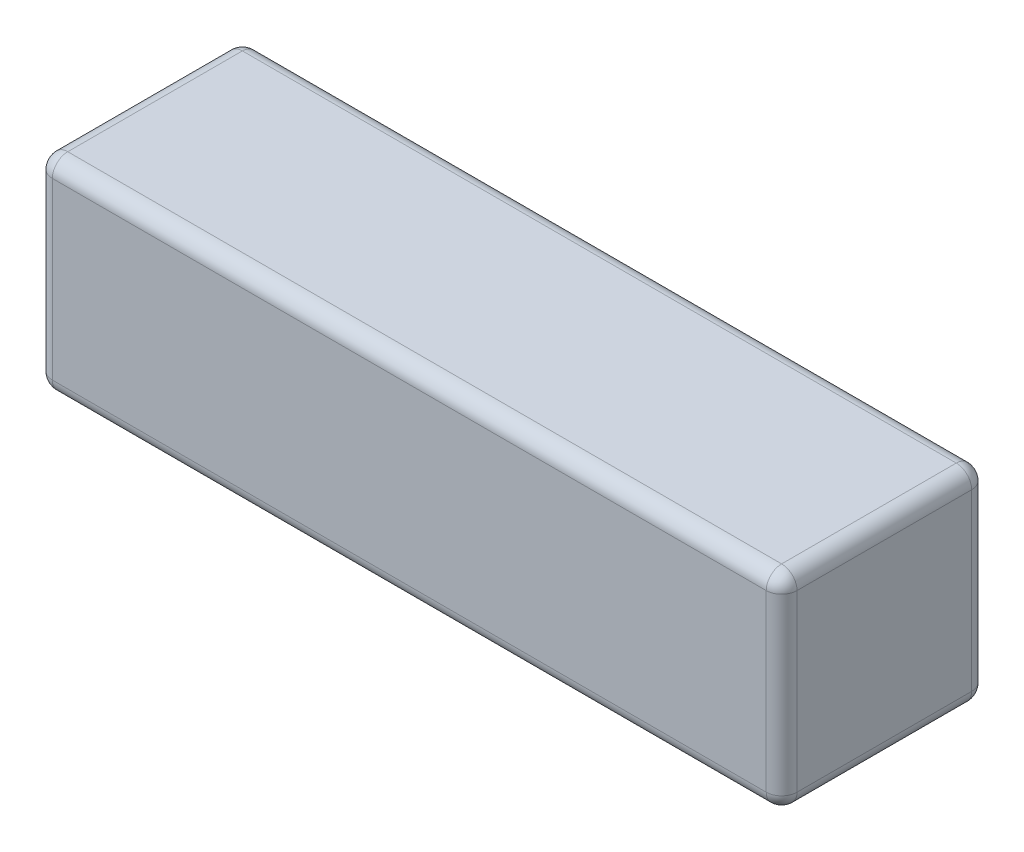
SolidWorks part; units mm, degrees
ref_plane "Front" through (0, 0, 0) normal (0, 0, 1) x (1, 0, 0)
ref_plane "Top" through (0, 0, 0) normal (0, 1, 0) x (1, 0, 0)
ref_plane "Right" through (0, 0, 0) normal (1, 0, 0) x (0, 0, -1)
sketch "草图1" plane through (0, 0, 0) normal (0, 1, 0) x (1, 0, 0)
  line L1 (72.5, -20) -> (-72.5, -20)
  line L2 (72.5, -20) -> (72.5, 20)
  line L3 (72.5, 20) -> (-72.5, 20)
  line L4 (-72.5, -20) -> (-72.5, 20)
  line L5 (72.5, -20) -> (-72.5, 20) construction
  line L6 (72.5, 20) -> (-72.5, -20) construction
  point P0 (0, 0)
  dimension "D1" = 145
  dimension "D2" = 40
extrude "凸台-拉伸1" add sketch "草图1" along normal blind 40
fillet "圆角1" radius 3 4 edges at (0, 0, -20) (0, 40, -20) (0, 0, 20) (0, 40, 20)
fillet "圆角2" radius 3 16 edges at (72.5, 0.8787, 19.1213) (72.5, 20, 20) (72.5, 39.1213, 19.1213) (72.5, 40, 0) (72.5, 39.1213, -19.1213) (72.5, 20, -20) (72.5, 0.8787, -19.1213) (72.5, 0, 0) (-72.5, 39.1213, -19.1213) (-72.5, 40, 0) (-72.5, 39.1213, 19.1213) (-72.5, 20, 20) (-72.5, 0.8787, 19.1213) (-72.5, 0, 0) (-72.5, 0.8787, -19.1213) (-72.5, 20, -20)
